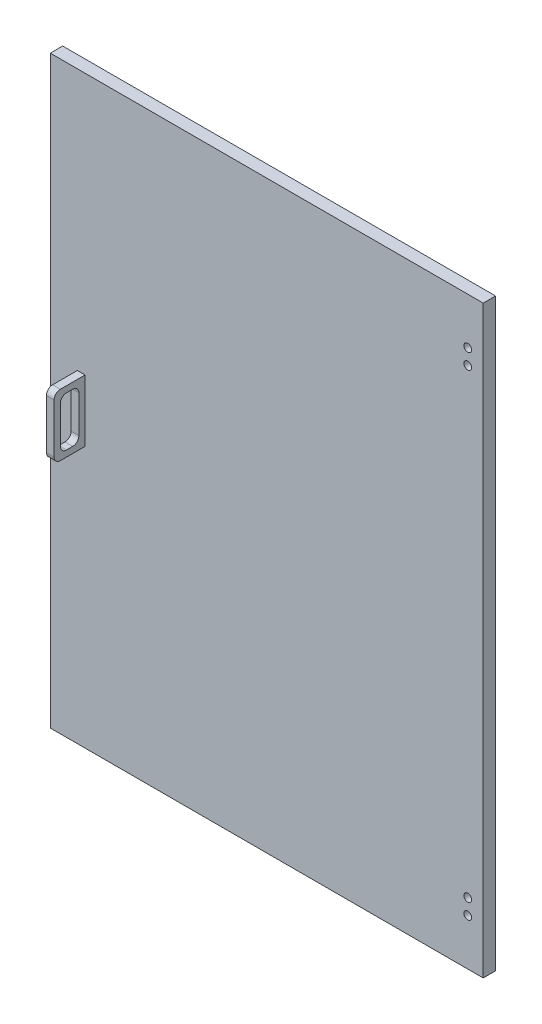
SolidWorks part; units mm, degrees
material "PVC 0.007 Plasticized"
ref_plane "Front Plane" through (0, 0, 0) normal (0, 0, 1) x (1, 0, 0)
ref_plane "Top Plane" through (0, 0, 0) normal (0, 1, 0) x (1, 0, 0)
ref_plane "Right Plane" through (0, 0, 0) normal (1, 0, 0) x (0, 0, -1)
sketch "Sketch1" plane through (0, 0, 0) normal (0, 0, 1) x (1, 0, 0)
  line L0 (-88.9, 120.015) -> (88.9, 120.015)
  line L7 (-88.9, 120.015) -> (-88.9, -120.015)
  line L8 (-88.9, -120.015) -> (88.9, -120.015)
  line L9 (88.9, 120.015) -> (88.9, -120.015)
  point P0 (0, 0)
  dimension "D1" = 240.03
  dimension "D2" = 177.8
  dimension "D3" = 88.9
  dimension "D4" = 120.015
extrude "Boss-Extrude1" add sketch "Sketch1" against normal blind 5.08
sketch "Sketch2" plane through (0, 0, 0) normal (0, 0, 1) x (1, 0, 0)
  line L0 (88.9, -120.015) -> (88.9, 120.015) construction
  line L1 (88.9, 120.015) -> (-88.9, 120.015) construction
  line L2 (55, 0) -> (-55, 0) construction
  circle A0 centre (82.55, 100.965) radius 1.5875
  circle A1 centre (82.55, 94.615) radius 1.5875
  circle A2 centre (82.55, -94.615) radius 1.5875
  circle A3 centre (82.55, -100.965) radius 1.5875
  point P10 (82.55, -94.615)
  dimension "D1" = 3.175
  dimension "D2" = 3.175
  dimension "D3" = 6.35
  dimension "D4" = 19.05
  dimension "D5" = 6.35
extrude "Cut-Extrude1" cut sketch "Sketch2" against normal through all
sketch "Sketch3" plane through (0, 0, 0) normal (0, 0, 1) x (1, 0, 0)
  line L0 (-77.7875, -12.7) -> (-74.6125, -12.7)
  line L1 (-77.7875, -12.7) -> (-77.7875, 12.7)
  line L2 (-77.7875, 12.7) -> (-74.6125, 12.7)
  line L3 (-74.6125, -12.7) -> (-74.6125, 12.7)
  line L4 (-77.7875, -12.7) -> (-74.6125, 12.7) construction
  line L5 (-77.7875, 12.7) -> (-74.6125, -12.7) construction
  line L6 (2.794, 0) -> (-2.794, 0) construction
  line L7 (-88.9, 120.015) -> (-88.9, -120.015) construction
  point P0 (-76.2, 0)
  dimension "D1" = 25.4
  dimension "D2" = 3.175
  dimension "D3" = 12.7
extrude "Boss-Extrude2" add sketch "Sketch3" along normal blind 12.7
sketch "Sketch4" plane through (-74.6125, 0, 0) normal (1, 0, 0) x (0, 0, -1)
  line L0 (9.779, 0) -> (-9.779, 0) construction
  line L1 (-10.16, -10.16) -> (-2.54, -10.16)
  line L2 (-10.16, -10.16) -> (-10.16, 10.16)
  line L3 (-10.16, 10.16) -> (-2.54, 10.16)
  line L4 (-2.54, -10.16) -> (-2.54, 10.16)
  line L5 (-10.16, -10.16) -> (-2.54, 10.16) construction
  line L6 (-10.16, 10.16) -> (-2.54, -10.16) construction
  line L7 (-12.7, -12.7) -> (-12.7, 12.7) construction
  line L8 (0, 143.3597) -> (0, -143.3597) construction
  line L9 (-12.7, 12.7) -> (0, 12.7) construction
  point P0 (-6.35, 0)
  dimension "D1" = 2.54
  dimension "D2" = 2.54
  dimension "D3" = 2.54
extrude "Cut-Extrude2" cut sketch "Sketch4" against normal through all
fillet "Fillet1" radius 2.54 6 edges at (-76.2, -12.7, 12.7) (-76.2, -10.16, 2.54) (-76.2, -10.16, 10.16) (-76.2, 10.16, 10.16) (-76.2, 10.16, 2.54) (-76.2, 12.7, 12.7)
